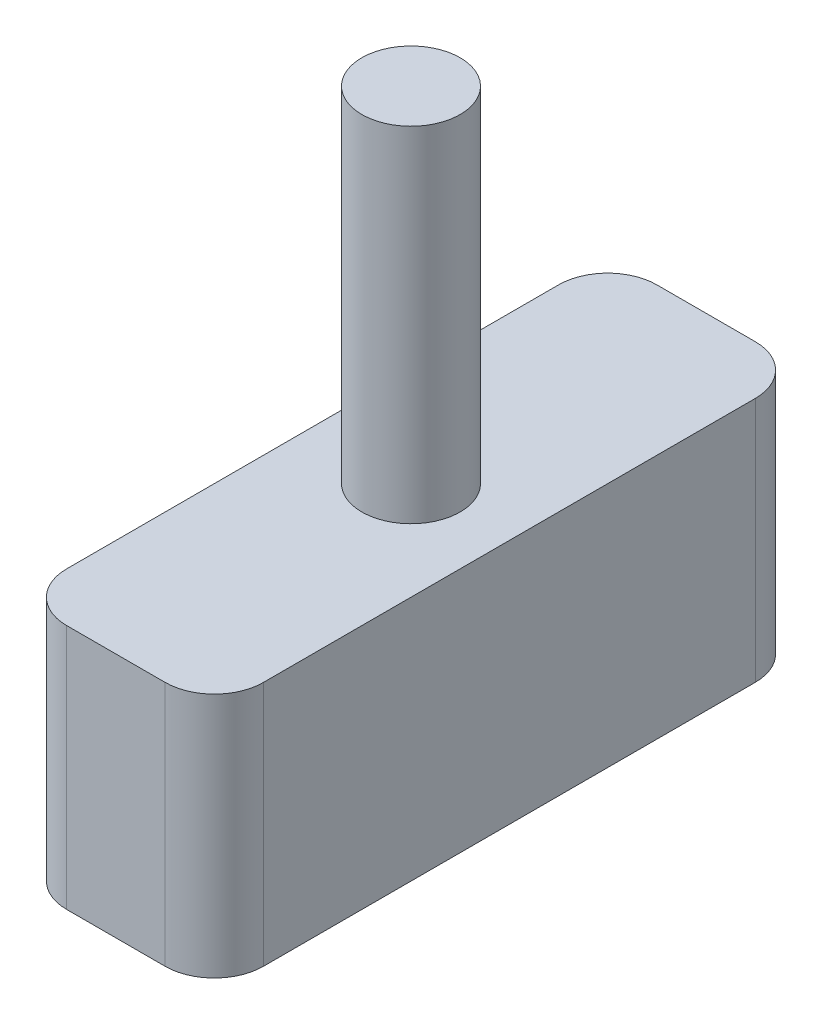
SolidWorks part; units mm, degrees
ref_plane "Front Plane" through (0, 0, 0) normal (0, 0, 1) x (1, 0, 0)
ref_plane "Top Plane" through (0, 0, 0) normal (0, 1, 0) x (1, 0, 0)
ref_plane "Right Plane" through (0, 0, 0) normal (1, 0, 0) x (0, 0, -1)
sketch "Sketch1" plane through (0, 0, 0) normal (0, 0, 1) x (1, 0, 0)
  line L1 (0, 7) -> (1, 7)
  line L2 (0, 7) -> (0, 0)
  line L3 (0, 0) -> (1, 0)
  line L4 (1, 7) -> (1, 0)
  dimension "D1" = 1
  dimension "D2" = 7
revolve "Revolve1" add sketch "Sketch1" angle 360 about L2
sketch "Sketch2" plane through (0, 0, 0) normal (0, -1, 0) x (1, 0, 0)
  line L1 (1, -6) -> (-1, -6)
  line L2 (2, -5) -> (2, 5)
  line L3 (1, 6) -> (-1, 6)
  line L4 (-2, -5) -> (-2, 5)
  line L5 (2, -6) -> (-2, 6) construction
  line L6 (2, 6) -> (-2, -6) construction
  arc A0 (-2, -5) -> (-1, -6) centre (-1, -5) ccw
  arc A1 (1, -6) -> (2, -5) centre (1, -5) ccw
  arc A2 (2, 5) -> (1, 6) centre (1, 5) ccw
  arc A3 (-2, 5) -> (-1, 6) centre (-1, 5) cw
  point P0 (0, 0)
  point P5 (0, -6)
  dimension "D3" = 1
  dimension "D1" = 12
  dimension "D2" = 4
extrude "Boss-Extrude1" add sketch "Sketch2" along normal blind 5 contours A3 L3 A2 L2 A1 L1 A0 L4
